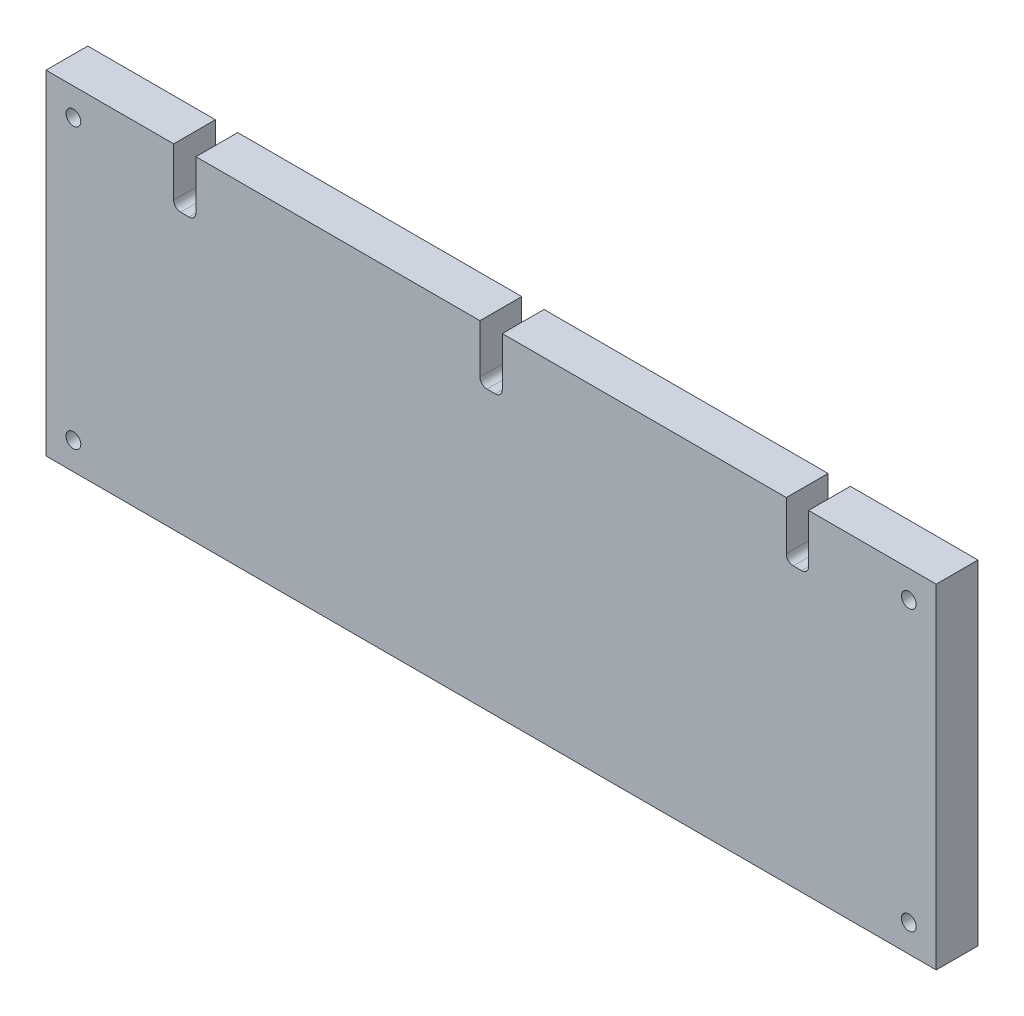
SolidWorks part; units mm, degrees
ref_plane "Front Plane" through (0, 0, 0) normal (0, 0, 1) x (1, 0, 0)
ref_plane "Top Plane" through (0, 0, 0) normal (0, 1, 0) x (1, 0, 0)
ref_plane "Right Plane" through (0, 0, 0) normal (1, 0, 0) x (0, 0, -1)
sketch "Sketch1" plane through (0, 0, 0) normal (0, 0, 1) x (1, 0, 0)
  line L0 (-432, -10.5371) -> (-432, 161.6719) construction
  line L1 (-229, -12.5) -> (-635, -12.5)
  line L2 (-229, -12.5) -> (-229, 139.9)
  line L3 (-229, 139.9) -> (-635, 139.9)
  line L4 (-635, -12.5) -> (-635, 139.9)
  line L5 (-254, -10.5371) -> (-610, -10.5371) construction
  line L6 (-245.8879, -12.5) -> (-252.0371, -12.5) construction
  line L7 (-432, -10.5371) -> (-432, -42.0383) construction
  line L9 (-229, 139.9) -> (-229, -12.5) construction
  circle A0 centre (-241.5, 0) radius 3.3655
  circle A1 centre (-622.5, 0) radius 3.3655
  point P4 (-432, -12.5)
  dimension "D2" = 6.731
  dimension "D1" = 152.4
extrude "Boss-Extrude1" add sketch "Sketch1" along normal blind 19.05
extrude "Cut-Extrude1" cut sketch "Sketch2" against normal up to surface (21.082 mm away) up to face at (-238.1345, 0, 19.05)
sketch "Sketch2" plane through (-432, 23.6125, -2.032) normal (0, 0, -1) x (-1, 0, 0)
  line L0 (-187.5822, 98.7314) -> (-193.4242, 108.85) construction
  circle A0 centre (-190.5032, 103.7907) radius 3.3655
ref_plane "Plane1" through (-432, 0, 0) normal (-1, 0, 0) x (0, 0, 1)
mirror "Mirror1" about plane through (-432, 0, 0) normal (-1, 0, 0) of "Cut-Extrude1"
sketch "Sketch3" plane through (0, 0, 19.05) normal (0, 0, 1) x (1, 0, 0)
  line L4 (-229, -12.5) -> (-229, 139.9)
  line L5 (-229, 139.9) -> (-635, 139.9)
  line L6 (-635, 139.9) -> (-635, -12.5)
  line L7 (-635, -12.5) -> (-229, -12.5)
  line L8 (-229, -12.5) -> (-229, 139.9)
  line L9 (-229, 139.9) -> (-635, 139.9)
  line L10 (-635, 139.9) -> (-635, -12.5)
  line L11 (-635, -12.5) -> (-229, -12.5)
  circle A0 centre (-241.4968, 127.4032) radius 3.3655 construction
  circle A1 centre (-241.5, 0) radius 3.3655 construction
  circle A2 centre (-622.5, 0) radius 3.3655 construction
  circle A3 centre (-622.5032, 127.4032) radius 3.3655 construction
  circle A4 centre (-241.4968, 127.4032) radius 3.3655
  circle A5 centre (-241.5, 0) radius 3.3655
  circle A6 centre (-622.5, 0) radius 3.3655
  circle A7 centre (-622.5032, 127.4032) radius 3.3655
  dimension "D1" = 0
sketch "Sketch4" plane through (0, 0, 19.05) normal (0, 0, 1) x (1, 0, 0)
  line L0 (-432, 139.9) -> (-432, -12.5) construction
  line L1 (-229, 139.9) -> (-635, 139.9) construction
  line L2 (-635, -12.5) -> (-229, -12.5) construction
  line L4 (-433.905, 114.5) -> (-430.095, 114.5)
  line L5 (-437.08, 117.675) -> (-437.08, 139.9)
  line L6 (-437.08, 139.9) -> (-426.92, 139.9)
  line L7 (-426.92, 117.675) -> (-426.92, 139.9)
  line L8 (-437.08, 114.5) -> (-426.92, 139.9) construction
  line L9 (-437.08, 139.9) -> (-426.92, 114.5) construction
  arc A0 (-433.905, 114.5) -> (-437.08, 117.675) centre (-433.905, 117.675) cw
  arc A1 (-430.095, 114.5) -> (-426.92, 117.675) centre (-430.095, 117.675) ccw
  point P6 (-432, 127.2)
  dimension "D3" = 3.175
  dimension "D1" = 10.16
  dimension "D2" = 25.4
extrude "Cut-Extrude2" cut sketch "Sketch4" against normal through all
pattern_linear "LPattern1" count 2 spacing 139.7 along (1, 0, 0) count 2 spacing 139.7 along (-1, 0, 0) of "Cut-Extrude2"
